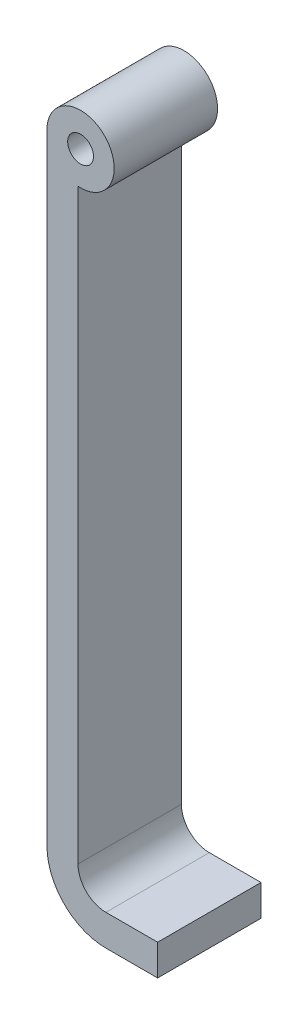
SolidWorks part; units mm, degrees
ref_plane "Front Plane" through (0, 0, 0) normal (0, 0, 1) x (1, 0, 0)
ref_plane "Top Plane" through (0, 0, 0) normal (0, 1, 0) x (1, 0, 0)
ref_plane "Right Plane" through (0, 0, 0) normal (1, 0, 0) x (0, 0, -1)
sketch "Sketch1" plane through (0, 0, 0) normal (0, 0, 1) x (1, 0, 0)
  line L0 (-3.25, 0) -> (-3.25, -60)
  line L2 (-0.25, -60) -> (-0.25, -3.2404)
  line L3 (2.45, -62.7) -> (7.45, -62.7)
  line L4 (7.45, -62.7) -> (7.45, -65.7)
  line L5 (7.45, -65.7) -> (2.45, -65.7)
  circle A0 centre (0, 0) radius 1.25
  arc A1 (-0.25, -3.2404) -> (-3.25, 0) centre (0, 0) ccw
  arc A2 (-3.25, -60) -> (2.45, -65.7) centre (2.45, -60) ccw
  arc A3 (-0.25, -60) -> (2.45, -62.7) centre (2.45, -60) ccw
  point P3 (-4.7, -60)
  point P9 (-1.7, -60)
  point P10 (-1.7, -60)
  point P13 (11.0747, -67.1701)
  dimension "D1" = 2.5
  dimension "D2" = 2
  dimension "D5" = 5.4
  dimension "D7" = 3
  dimension "D3" = 3
  dimension "D4" = 60
  dimension "D6" = 5
extrude "Boss-Extrude1" add sketch "Sketch1" along normal blind 10
